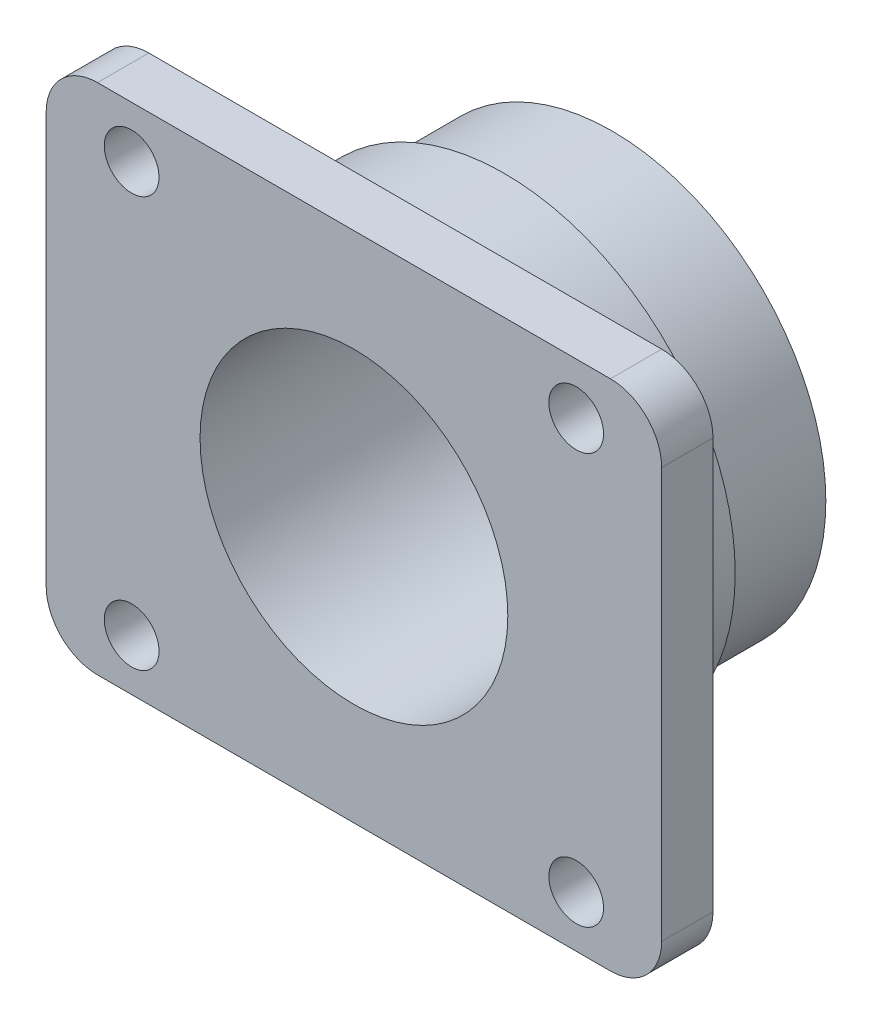
SolidWorks part; units mm, degrees
material "6061 合金"
ref_plane "前视基准面" through (0, 0, 0) normal (0, 0, 1) x (1, 0, 0)
ref_plane "上视基准面" through (0, 0, 0) normal (0, 1, 0) x (1, 0, 0)
ref_plane "右视基准面" through (0, 0, 0) normal (1, 0, 0) x (0, 0, -1)
sketch "草图1" plane through (0, 0, 0) normal (0, 0, 1) x (1, 0, 0)
  circle A0 centre (0, 0) radius 9
  circle A1 centre (0, 0) radius 12.5
  dimension "D1" = 18
  dimension "D2" = 25
extrude "凸台-拉伸1" add sketch "草图1" along normal blind 6.3
sketch "草图2" plane through (0, 0, 6.3) normal (0, 0, 1) x (1, 0, 0)
  circle A0 centre (0, 0) radius 9 construction
  circle A1 centre (0, 0) radius 9
  circle A2 centre (0, 0) radius 13.5
  dimension "D1" = 27
extrude "凸台-拉伸2" add sketch "草图2" along normal blind 5.8
sketch "草图3" plane through (0, 0, 12.1) normal (0, 0, 1) x (1, 0, 0)
  line L0 (-18, 15) -> (-18, -15)
  line L1 (-18, -15) -> (18, -15)
  line L2 (18, -15) -> (18, 15)
  line L3 (18, 15) -> (-18, 15)
  line L4 (0, 0) -> (-4.0071, 0) construction
  line L5 (0, 0) -> (0, -28.5339) construction
  circle A0 centre (0, 0) radius 9 construction
  circle A1 centre (0, 0) radius 9
  circle A2 centre (13, 12) radius 1.6
  circle A3 centre (13, -12) radius 1.6
  circle A4 centre (-13, -12) radius 1.6
  circle A5 centre (-13, 12) radius 1.6
  dimension "D5" = 3.2
  dimension "D1" = 18
  dimension "D2" = 18
  dimension "D3" = 15
  dimension "D4" = 15
  dimension "D6" = 13
  dimension "D7" = 12
extrude "凸台-拉伸3" add sketch "草图3" along normal blind 3
fillet "圆角1" radius 3 4 edges at (18, -15, 13.6) (-18, -15, 13.6) (-18, 15, 13.6) (18, 15, 13.6)
